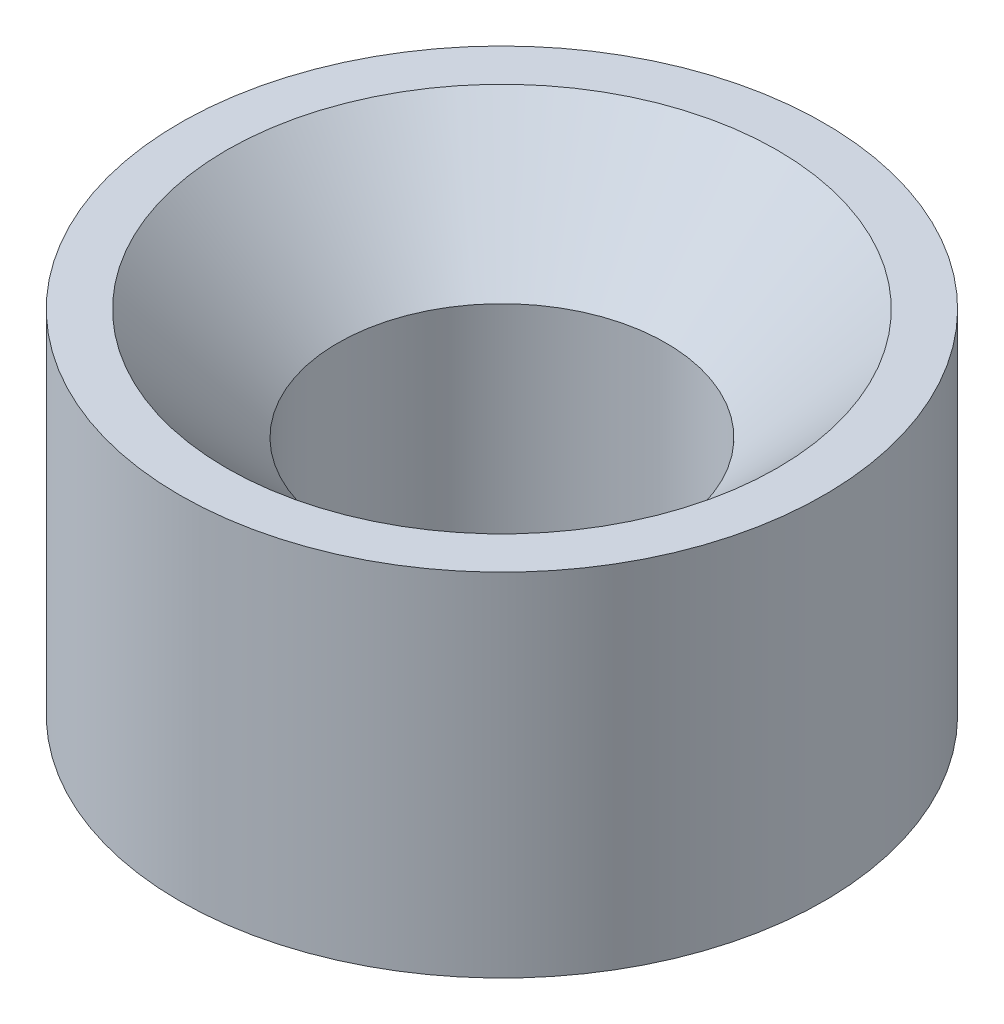
SolidWorks part; units mm, degrees
ref_plane "Front Plane" through (0, 0, 0) normal (0, 0, 1) x (1, 0, 0)
ref_plane "Top Plane" through (0, 0, 0) normal (0, 1, 0) x (1, 0, 0)
ref_plane "Right Plane" through (0, 0, 0) normal (1, 0, 0) x (0, 0, -1)
sketch "Sketch1" plane through (0, 0, 0) normal (0, 1, 0) x (1, 0, 0)
  circle A0 centre (0, 0) radius 2.75
  circle A1 centre (0, 0) radius 1.4
  dimension "D1" = 5.5
  dimension "D2" = 2.8
extrude "Boss-Extrude1" add sketch "Sketch1" along normal mid plane 3
chamfer "Chamfer1" distance 0.95 angle 45 1 edges at (0, 1.5, 1.4)
